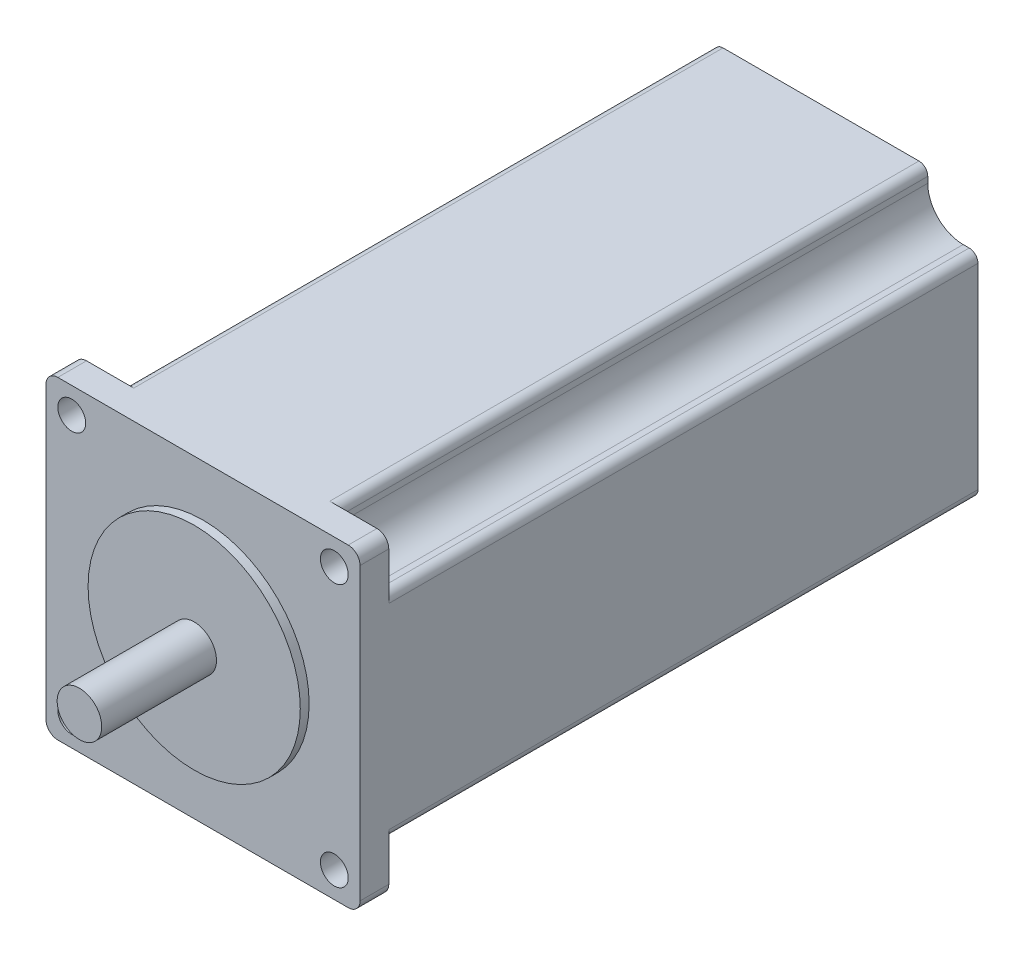
SolidWorks part; units mm, degrees
ref_plane "Front Plane" through (0, 0, 0) normal (0, 0, 1) x (1, 0, 0)
ref_plane "Top Plane" through (0, 0, 0) normal (0, 1, 0) x (1, 0, 0)
ref_plane "Right Plane" through (0, 0, 0) normal (1, 0, 0) x (0, 0, -1)
sketch "Sketch1" plane through (0, 0, 0) normal (0, 0, 1) x (1, 0, 0)
  line L0 (-7.9293, 43.8002) -> (-7.9293, -48.6721) construction
  line L1 (-50.7782, 0) -> (43.3245, 0) construction
  line L2 (-34.0024, 28.194) -> (18.1438, 28.194)
  line L3 (20.2647, 26.0731) -> (20.2647, -26.0731)
  line L4 (-36.1233, 26.0731) -> (-36.1233, -26.0731)
  line L5 (-34.0024, -28.194) -> (18.1438, -28.194)
  circle A0 centre (15.6419, 23.5712) radius 2.5019
  arc A1 (20.2647, 26.0731) -> (18.1438, 28.194) centre (18.1438, 26.0731) ccw
  arc A2 (-36.1233, 26.0731) -> (-34.0024, 28.194) centre (-34.0024, 26.0731) cw
  circle A3 centre (-31.5005, 23.5712) radius 2.5019
  circle A4 centre (-31.5005, -23.5712) radius 2.5019
  arc A5 (-36.1233, -26.0731) -> (-34.0024, -28.194) centre (-34.0024, -26.0731) ccw
  arc A6 (20.2647, -26.0731) -> (18.1438, -28.194) centre (18.1438, -26.0731) cw
  circle A7 centre (15.6419, -23.5712) radius 2.5019
  point P6 (-7.9293, -28.194)
  point P17 (20.2647, 0)
  point P18 (-7.9293, 28.194)
  point P28 (-36.1233, 0)
  dimension "D3" = 5.0038
  dimension "D4" = 47.1424
  dimension "D5" = 47.1424
  dimension "D6" = 2.1209
  dimension "D1" = 56.388
  dimension "D2" = 56.388
extrude "Boss-Extrude1" add sketch "Sketch1" along normal blind 110.9472
sketch "Sketch2" plane through (0, 0, 110.9472) normal (0, 0, 1) x (1, 0, 0)
  line L2 (-36.1233, 26.0731) -> (-36.1233, -26.0731) construction
  line L3 (18.1438, 28.194) -> (-34.0024, 28.194) construction
  circle A0 centre (-7.9293, 0) radius 19.05
  point P4 (-36.1233, 0)
  point P7 (-7.9293, 28.194)
  dimension "D1" = 38.1
extrude "Boss-Extrude2" add sketch "Sketch2" along normal blind 1.5875
sketch "Sketch3" plane through (0, 0, 112.5347) normal (0, 0, 1) x (1, 0, 0)
  circle A0 centre (-7.9293, 0) radius 4.0005
  dimension "D1" = 8.001
extrude "Boss-Extrude3" add sketch "Sketch3" along normal blind 20.5994
sketch "Sketch4" plane through (0, 0, 0) normal (0, 0, -1) x (-1, 0, 0)
  line L0 (34.5358, -19.177) -> (33.4563, -19.177)
  line L1 (27.1063, -25.527) -> (27.1063, -26.6065)
  line L2 (25.5188, -28.194) -> (18.6772, -28.194)
  line L3 (18.6772, -28.194) -> (18.6772, -39.08)
  line L4 (18.6772, -39.08) -> (53.3239, -39.08)
  line L5 (53.3239, -39.08) -> (53.3239, -7.6673)
  line L6 (53.3239, -7.6673) -> (36.1233, -7.6673)
  line L7 (36.1233, -7.6673) -> (36.1233, -17.5895)
  line L8 (34.0024, -28.194) -> (-18.1438, -28.194) construction
  line L9 (36.1233, 26.0731) -> (36.1233, -26.0731) construction
  line L10 (-20.2647, 0) -> (74.3745, 0) construction
  line L11 (-20.2647, -26.0731) -> (-20.2647, 26.0731) construction
  line L12 (7.9293, -28.194) -> (7.9293, 21.4382) construction
  line L13 (36.1233, 7.6673) -> (36.1233, 17.5895)
  line L14 (53.3239, 7.6673) -> (36.1233, 7.6673)
  line L15 (53.3239, 39.08) -> (53.3239, 7.6673)
  line L16 (18.6772, 39.08) -> (53.3239, 39.08)
  line L17 (18.6772, 28.194) -> (18.6772, 39.08)
  line L18 (25.5188, 28.194) -> (18.6772, 28.194)
  line L19 (27.1063, 25.527) -> (27.1063, 26.6065)
  line L20 (34.5358, 19.177) -> (33.4563, 19.177)
  line L21 (-18.6772, 19.177) -> (-17.5977, 19.177)
  line L22 (-11.2477, 25.527) -> (-11.2477, 26.6065)
  line L23 (-9.6602, 28.194) -> (-2.8186, 28.194)
  line L24 (-2.8186, 28.194) -> (-2.8186, 39.08)
  line L25 (-2.8186, 39.08) -> (-37.4653, 39.08)
  line L26 (-37.4653, 39.08) -> (-37.4653, 7.6673)
  line L27 (-37.4653, 7.6673) -> (-20.2647, 7.6673)
  line L28 (-20.2647, 7.6673) -> (-20.2647, 17.5895)
  line L29 (-20.2647, -7.6673) -> (-20.2647, -17.5895)
  line L30 (-37.4653, -7.6673) -> (-20.2647, -7.6673)
  line L31 (-37.4653, -39.08) -> (-37.4653, -7.6673)
  line L32 (-2.8186, -39.08) -> (-37.4653, -39.08)
  line L33 (-2.8186, -28.194) -> (-2.8186, -39.08)
  line L34 (-9.6602, -28.194) -> (-2.8186, -28.194)
  line L35 (-11.2477, -25.527) -> (-11.2477, -26.6065)
  line L36 (-18.6772, -19.177) -> (-17.5977, -19.177)
  arc A0 (27.1063, -25.527) -> (33.4563, -19.177) centre (33.4563, -25.527) cw
  arc A1 (34.5358, -19.177) -> (36.1233, -17.5895) centre (34.5358, -17.5895) ccw
  arc A2 (25.5188, -28.194) -> (27.1063, -26.6065) centre (25.5188, -26.6065) ccw
  arc A3 (25.5188, 28.194) -> (27.1063, 26.6065) centre (25.5188, 26.6065) cw
  arc A4 (34.5358, 19.177) -> (36.1233, 17.5895) centre (34.5358, 17.5895) cw
  arc A5 (27.1063, 25.527) -> (33.4563, 19.177) centre (33.4563, 25.527) ccw
  arc A6 (-11.2477, 25.527) -> (-17.5977, 19.177) centre (-17.5977, 25.527) cw
  arc A7 (-18.6772, 19.177) -> (-20.2647, 17.5895) centre (-18.6772, 17.5895) ccw
  arc A8 (-9.6602, 28.194) -> (-11.2477, 26.6065) centre (-9.6602, 26.6065) ccw
  arc A9 (-9.6602, -28.194) -> (-11.2477, -26.6065) centre (-9.6602, -26.6065) cw
  arc A10 (-18.6772, -19.177) -> (-20.2647, -17.5895) centre (-18.6772, -17.5895) cw
  arc A11 (-11.2477, -25.527) -> (-17.5977, -19.177) centre (-17.5977, -25.527) ccw
  dimension "D5" = 6.35
  dimension "D6" = 1.5875
  dimension "D1" = 9.017
  dimension "D2" = 9.017
  dimension "D3" = 0
  dimension "D4" = 0
extrude "Cut-Extrude1" cut sketch "Sketch4" against normal blind 105.791
